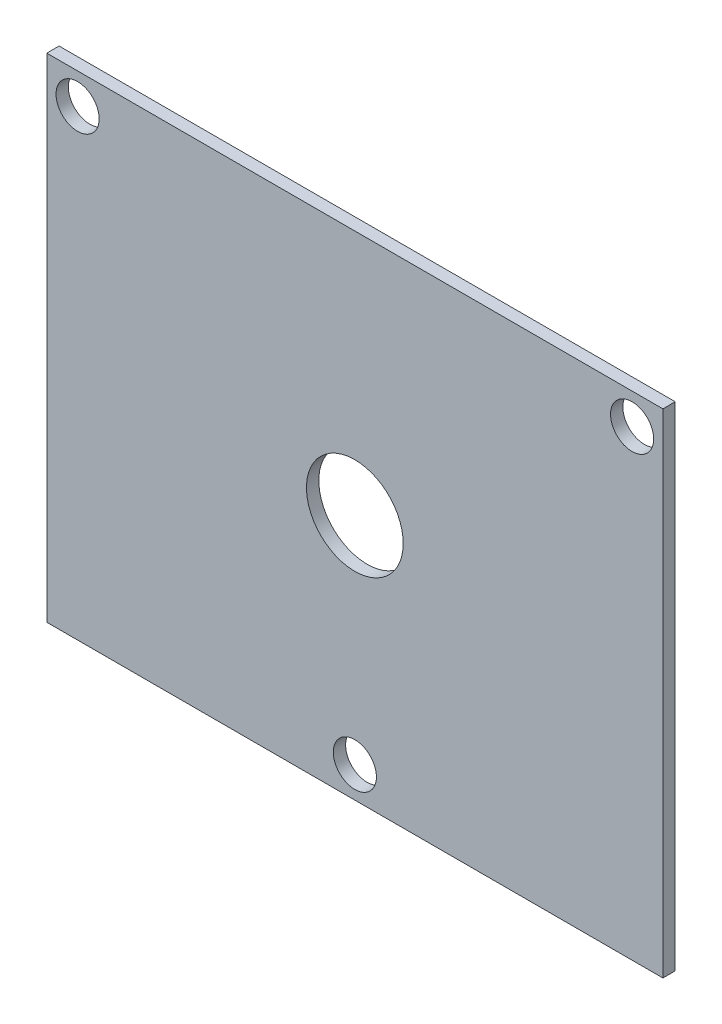
SolidWorks part; units mm, degrees
ref_plane "Front Plane" through (0, 0, 0) normal (0, 0, 1) x (1, 0, 0)
ref_plane "Top Plane" through (0, 0, 0) normal (0, 1, 0) x (1, 0, 0)
ref_plane "Right Plane" through (0, 0, 0) normal (1, 0, 0) x (0, 0, -1)
sketch "Sketch2" plane through (0, 0, 0) normal (0, 0, 1) x (1, 0, 0)
  line L1 (0, 0) -> (254, 0)
  line L2 (0, 0) -> (0, 203.2)
  line L3 (0, 203.2) -> (254, 203.2)
  line L4 (254, 0) -> (254, 203.2)
  dimension "D1" = 203.2
  dimension "D2" = 254
extrude "Boss-Extrude1" add sketch "Sketch2" along normal blind 5.08
sketch "Sketch3" plane through (0, 0, 5.08) normal (0, 0, 1) x (1, 0, 0)
  line L0 (254, 203.2) -> (0, 203.2) construction
  line L1 (0, 203.2) -> (0, 0) construction
  line L2 (254, 0) -> (254, 203.2) construction
  line L3 (0, 0) -> (254, 0) construction
  circle A0 centre (12.7, 190.5) radius 8.89
  circle A1 centre (241.3, 190.5) radius 8.89
  circle A2 centre (127, 12.7) radius 8.89
  dimension "D1" = 17.78
  dimension "D2" = 17.78
  dimension "D3" = 17.78
  dimension "D4" = 12.7
  dimension "D5" = 12.7
  dimension "D6" = 12.7
  dimension "D7" = 12.7
  dimension "D8" = 12.7
  dimension "D9" = 127
sketch "Sketch4" plane through (0, 0, 5.08) normal (0, 0, 1) x (1, 0, 0)
  line L0 (254, 203.2) -> (0, 203.2) construction
  line L1 (0, 203.2) -> (0, 0) construction
  circle A0 centre (127, 101.6) radius 19.939
  dimension "D1" = 39.878
  dimension "D2" = 101.6
  dimension "D3" = 127
extrude "Cut-Extrude2" cut sketch "Sketch4" against normal through all
extrude "Cut-Extrude3" cut sketch "Sketch3" against normal through all
equation "\"FoamCore\" = \".2\""
equation "\"MDF\" = \".2\""
equation "\"GMaterial\"= \".2\""
equation "\"BaseWidth\" = \"10in\""
equation "\"BaseLength\" = \"8in\""
equation "\"D1@Sketch2\"=\"BaseLength\""
equation "\"D2@Sketch2\"=\"BaseWidth\""
equation "\"D1@Boss-Extrude1\"=\"GMaterial\""
equation "\"D1@Sketch3\"=\"PVCMountDiameter\" +\"PVCThickness\""
equation "\"D2@Sketch3\"=\"PVCMountDiameter\" + \"PVCThickness\""
equation "\"D3@Sketch3\"=\"PVCMountDiameter\" +\"PVCThickness\""
equation "\"D4@Sketch3\" = \"PVCMountDistanceToEdge\""
equation "\"D5@Sketch3\" = \"PVCMountDistanceToEdge\""
equation "\"D6@Sketch3\" = \"PVCMountDistanceToEdge\""
equation "\"D7@Sketch3\" = \"PVCMountDistanceToEdge\""
equation "\"D8@Sketch3\" = \"PVCMountDistanceToEdge\""
equation "\"D9@Sketch3\"=\"BaseWidth\" /2"
equation "\"BallDiameter\" = \"1.57in\""
equation "\"D1@Sketch4\"=\"BallDiameter\""
equation "\"D2@Sketch4\"=\"BaseLength\" /2"
equation "\"D3@Sketch4\"=\"BaseWidth\" /2"
equation "\"PVCMountDiameter\" = \"0.5in\""
equation "\"PVCMountDistanceToEdge\" = \"0.5\""
equation "\"BaseGap\" = \"4in\""
equation "\"FunnelTopDiameter\" = \"8in\""
equation "\"FunnelTopDepth\" = \"1.5in\""
equation "\"BallGap\" = \"0.1in\""
equation "\"FunnelLength\" = 6in"
equation "\"FunnelMaterial\" = 0.1in"
equation "\"FunnelLowerDiameter\" = \"BallDiameter\"+\"BallGap\""
equation "\"FunnelDepth\" = 1.5in"
equation "\"PVCThickness\" = \"0.2in\""
equation "\"AmmoFeederLength\" = 8in "
equation "\"PVCdiameter\" = \"0.5\""
equation "\"PVCmountdistance\" = \"0.5\""
